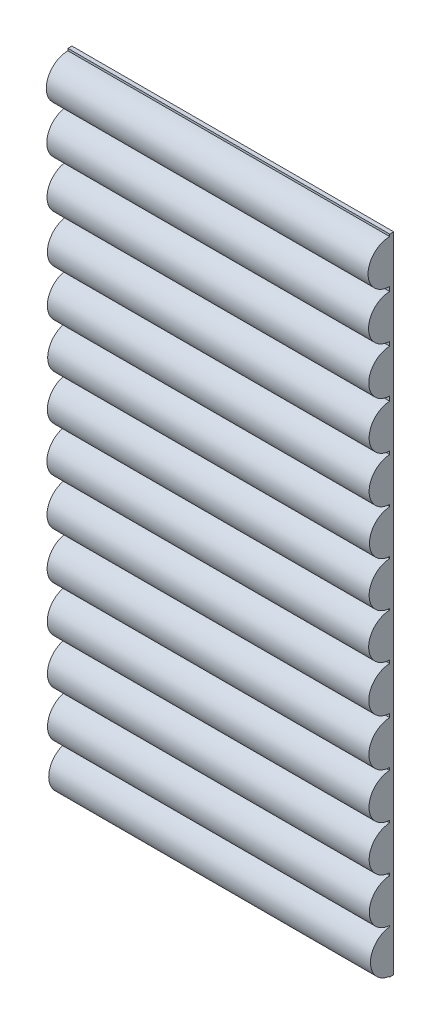
SolidWorks part; units mm, degrees
ref_plane "前视基准面" through (0, 0, 0) normal (0, 0, 1) x (1, 0, 0)
ref_plane "上视基准面" through (0, 0, 0) normal (0, 1, 0) x (1, 0, 0)
ref_plane "右视基准面" through (0, 0, 0) normal (1, 0, 0) x (0, 0, -1)
sketch "草图1" plane through (0, 0, 0) normal (0, 0, 1) x (1, 0, 0)
  line L1 (0, 0) -> (2.08, 0)
  line L2 (0, 0) -> (0, 4.16)
  line L3 (0, 4.16) -> (2.08, 4.16)
  line L4 (2.08, 0) -> (2.08, 4.16)
extrude "凸台-拉伸1" add sketch "草图1" along normal blind 0.026
sketch "草图2" plane through (0, 0, 0) normal (-1, 0, 0) x (0, 0, 1)
  line L0 (0.026, 4.16) -> (0.026, 0) construction
  line L1 (0.026, 4.1462) -> (0.026, 3.8669)
  line L2 (0.023, 3.8388) -> (0.023, 3.5595)
  line L3 (0.0215, 3.5328) -> (0.0215, 3.2535)
  line L4 (0.0192, 3.2246) -> (0.0192, 2.9453)
  line L5 (0.0192, 2.9255) -> (0.0192, 2.6461)
  line L6 (0.017, 2.6338) -> (0.017, 2.3545)
  line L7 (0.0192, 2.3437) -> (0.0192, 2.0643)
  line L8 (0.0222, 2.055) -> (0.0222, 1.7757)
  line L9 (0.0215, 1.7558) -> (0.0215, 1.4765)
  line L10 (0.0207, 1.4529) -> (0.0207, 1.1736)
  line L11 (0.0201, 1.1578) -> (0.0201, 0.8785)
  line L12 (0.0189, 0.8639) -> (0.0189, 0.5846)
  line L13 (0.0183, 0.5687) -> (0.0183, 0.2894)
  line L14 (0.0104, 0.2833) -> (0.0104, 0.004)
  arc A0 (0.026, 3.8669) -> (0.026, 4.1462) centre (0.026, 4.0065) ccw
  arc A1 (0.023, 3.5595) -> (0.023, 3.8388) centre (0.023, 3.6991) ccw
  arc A2 (0.0215, 3.2535) -> (0.0215, 3.5328) centre (0.0215, 3.3932) ccw
  arc A3 (0.0192, 2.9453) -> (0.0192, 3.2246) centre (0.0192, 3.085) ccw
  arc A4 (0.0192, 2.6461) -> (0.0192, 2.9255) centre (0.0192, 2.7858) ccw
  arc A5 (0.017, 2.3545) -> (0.017, 2.6338) centre (0.017, 2.4941) ccw
  arc A6 (0.0192, 2.0643) -> (0.0192, 2.3437) centre (0.0192, 2.204) ccw
  arc A7 (0.0222, 1.7757) -> (0.0222, 2.055) centre (0.0222, 1.9153) ccw
  arc A8 (0.0215, 1.4765) -> (0.0215, 1.7558) centre (0.0215, 1.6162) ccw
  arc A9 (0.0207, 1.1736) -> (0.0207, 1.4529) centre (0.0207, 1.3132) ccw
  arc A10 (0.0201, 0.8785) -> (0.0201, 1.1578) centre (0.0201, 1.0181) ccw
  arc A11 (0.0189, 0.5846) -> (0.0189, 0.8639) centre (0.0189, 0.7243) ccw
  arc A12 (0.0183, 0.2894) -> (0.0183, 0.5687) centre (0.0183, 0.429) ccw
  arc A13 (0.0104, 0.004) -> (0.0104, 0.2833) centre (0.0104, 0.1436) ccw
extrude "凸台-拉伸2" add sketch "草图2" against normal up to surface (2.08 mm away) up to face at (2.08, 2.08, 0.013)
